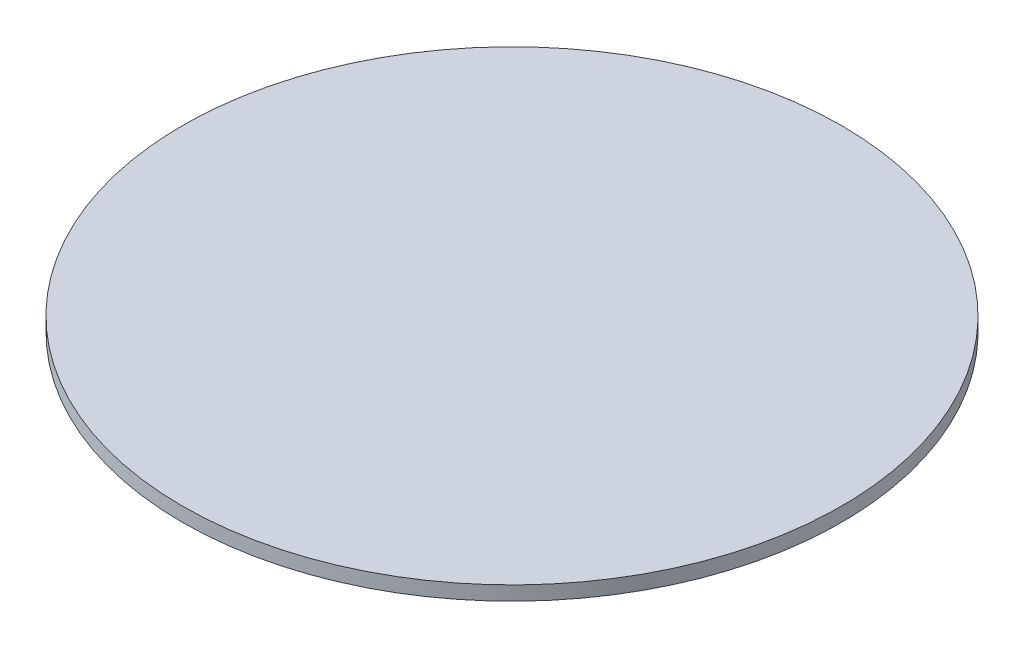
SolidWorks part; units mm, degrees
ref_plane "Front Plane" through (0, 0, 0) normal (0, 0, 1) x (1, 0, 0)
ref_plane "Top Plane" through (0, 0, 0) normal (0, 1, 0) x (1, 0, 0)
ref_plane "Right Plane" through (0, 0, 0) normal (1, 0, 0) x (0, 0, -1)
sketch "Sketch1" plane through (0, 0, 0) normal (0, 1, 0) x (1, 0, 0)
  circle A0 centre (0, 0) radius 70
  dimension "D1" = 140
extrude "Boss-Extrude1" add sketch "Sketch1" along normal blind 3
sketch "Sketch2" plane through (0, 3, 0) normal (0, 1, 0) x (1, 0, 0)
  line L0 (-70, 0) -> (70, 0) construction
  line L1 (0, 70) -> (0, -70) construction
  circle A0 centre (0, 0) radius 70 construction
  circle A1 centre (0, 0) radius 70 construction
  point P0 (70, 0)
  point P1 (-70, 0)
  point P6 (0, 0)
sketch "Sketch3" plane through (0, 0, 0) normal (0, -1, 0) x (1, 0, 0)
  line L0 (0, -70) -> (0, 70) construction
  line L1 (70, 0) -> (-70, 0) construction
  circle A0 centre (0, 0) radius 70 construction
